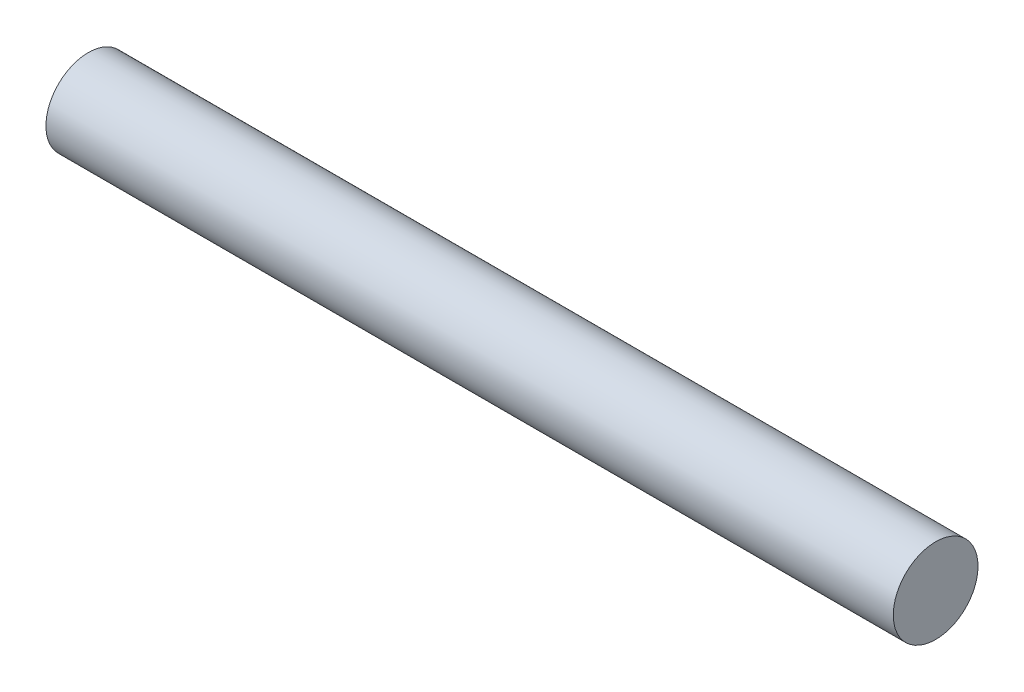
SolidWorks part; units mm, degrees
material "AISI 1045 Steel, cold drawn"
ref_plane "Front Plane" through (0, 0, 0) normal (0, 0, 1) x (1, 0, 0)
ref_plane "Top Plane" through (0, 0, 0) normal (0, 1, 0) x (1, 0, 0)
ref_plane "Right Plane" through (0, 0, 0) normal (1, 0, 0) x (0, 0, -1)
sketch "Sketch1" plane through (0, 0, 0) normal (1, 0, 0) x (0, 0, -1)
  circle A2 centre (0, 0) radius 3.175
  dimension "D1" = 6.35
extrude "Boss-Extrude1" add sketch "Sketch1" along normal blind 63.5
chamfer "Chamfer1" [suppressed] distance 0.254 angle 45
sketch "Sketch2" [suppressed] plane through (63.5, 0, 0) normal (1, 0, 0) x (0, 0, -1)
  line L0 (-1.5875, 2.7496) -> (1.5875, 2.7496)
  circle A0 centre (0, 0) radius 3.175 construction
  arc A1 (1.5875, 2.7496) -> (-1.5875, 2.7496) centre (0, 0) ccw
  dimension "D1" = 3.175
extrude "Cut-Extrude2" [suppressed] cut sketch "Sketch2" against normal through all
